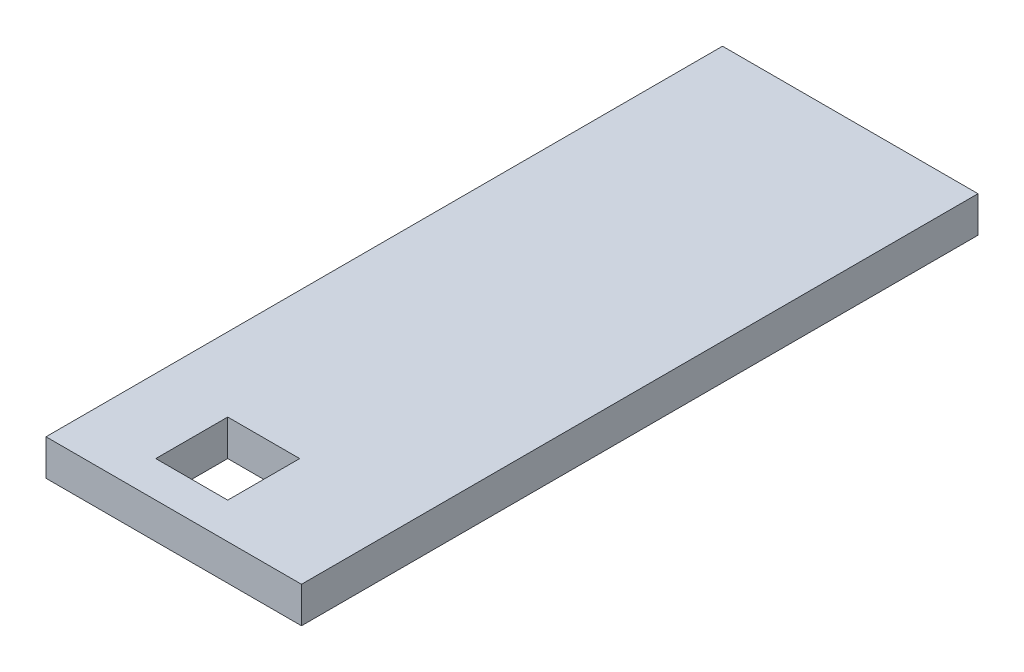
SolidWorks part; units mm, degrees
ref_plane "Front Plane" through (0, 0, 0) normal (0, 0, 1) x (1, 0, 0)
ref_plane "Top Plane" through (0, 0, 0) normal (0, 1, 0) x (1, 0, 0)
ref_plane "Right Plane" through (0, 0, 0) normal (1, 0, 0) x (0, 0, -1)
sketch "Sketch1" plane through (0, 0, 0) normal (0, 0, 1) x (1, 0, 0)
  line L1 (0, 0) -> (355, 0)
  line L2 (0, 0) -> (0, 50)
  line L3 (0, 50) -> (355, 50)
  line L4 (355, 0) -> (355, 50)
  dimension "D1" = 50
  dimension "D2" = 355
extrude "Boss-Extrude1" add sketch "Sketch1" along normal blind 940
sketch "Sketch2" plane through (0, 50, 0) normal (0, 1, 0) x (1, 0, 0)
  line L1 (202.5, -890) -> (102.5, -890)
  line L2 (202.5, -890) -> (202.5, -790)
  line L3 (202.5, -790) -> (102.5, -790)
  line L4 (102.5, -890) -> (102.5, -790)
  line L5 (355, -940) -> (355, 0) construction
  line L6 (355, -940) -> (0, -940) construction
  dimension "D1" = 100
  dimension "D2" = 152.5
  dimension "D3" = 50
extrude "Cut-Extrude1" cut sketch "Sketch2" against normal through all
